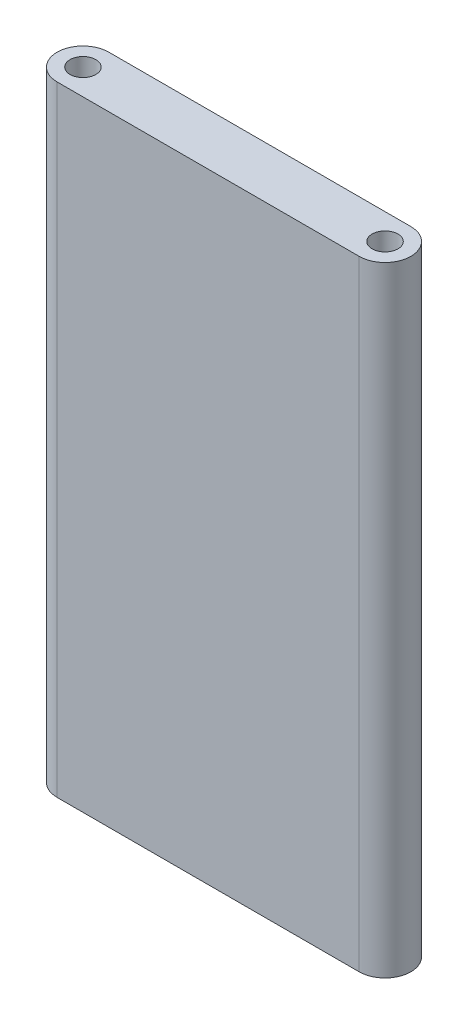
SolidWorks part; units mm, degrees
ref_plane "Front Plane" through (0, 0, 0) normal (0, 0, 1) x (1, 0, 0)
ref_plane "Top Plane" through (0, 0, 0) normal (0, 1, 0) x (1, 0, 0)
ref_plane "Right Plane" through (0, 0, 0) normal (1, 0, 0) x (0, 0, -1)
sketch "Sketch1" plane through (0, 0, 0) normal (0, 1, 0) x (1, 0, 0)
  line L0 (-37.1475, 0) -> (37.1475, 0) construction
  line L1 (-37.1475, 6.35) -> (37.1475, 6.35)
  line L2 (-37.1475, -6.35) -> (37.1475, -6.35)
  circle A1 centre (37.1475, 0) radius 3.175
  circle A2 centre (-37.1475, 0) radius 3.175
  arc A3 (-37.1475, 6.35) -> (-37.1475, -6.35) centre (-37.1475, 0) ccw
  arc A4 (37.1475, -6.35) -> (37.1475, 6.35) centre (37.1475, 0) ccw
  circle A5 centre (0, 0) radius 49.53 construction
  point P7 (0, 0)
  dimension "D1" = 74.295
  dimension "D2" = 6.35
  dimension "D3" = 99.06
  dimension "D4" = 12.7
extrude "Boss-Extrude1" add sketch "Sketch1" along normal blind 152.4
